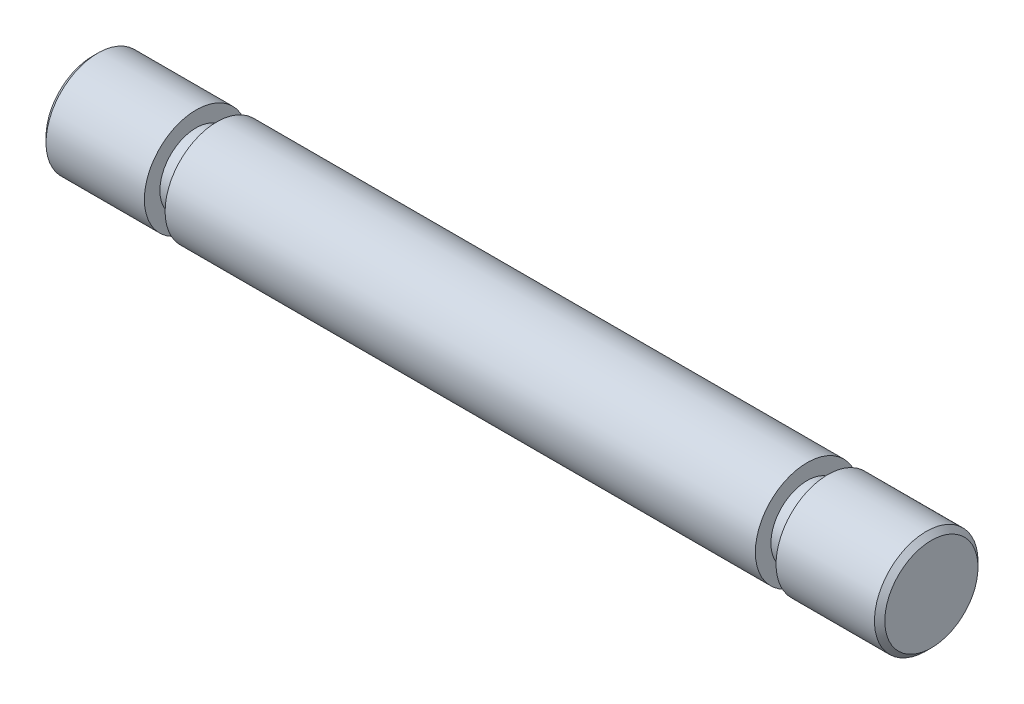
SolidWorks part; units mm, degrees
ref_plane "前视基准面" through (0, 0, 0) normal (0, 0, 1) x (1, 0, 0)
ref_plane "上视基准面" through (0, 0, 0) normal (0, 1, 0) x (1, 0, 0)
ref_plane "右视基准面" through (0, 0, 0) normal (1, 0, 0) x (0, 0, -1)
sketch "草图4" plane through (0, 0, 0) normal (1, 0, 0) x (0, 0, -1)
  circle A0 centre (0, 0) radius 5
  dimension "D1" = 10
extrude "凸台-拉伸4" add sketch "草图4" along normal blind 57
sketch "草图5" plane through (0, 0, 0) normal (-1, 0, 0) x (0, 0, 1)
  circle A0 centre (0, 0) radius 3.5
  dimension "D1" = 7
extrude "凸台-拉伸5" add sketch "草图5" along normal blind 2
sketch "草图6" plane through (-2, 0, 0) normal (-1, 0, 0) x (0, 0, 1)
  circle A0 centre (0, 0) radius 5
  dimension "D1" = 10
extrude "凸台-拉伸6" add sketch "草图6" along normal blind 10
sketch "草图7" plane through (57, 0, 0) normal (1, 0, 0) x (0, 0, -1)
  circle A0 centre (0, 0) radius 3.5
  dimension "D1" = 7
extrude "凸台-拉伸7" add sketch "草图7" along normal blind 2
sketch "草图8" plane through (59, 0, 0) normal (1, 0, 0) x (0, 0, -1)
  circle A0 centre (0, 0) radius 5
  dimension "D1" = 10
extrude "凸台-拉伸8" add sketch "草图8" along normal blind 10
chamfer "倒角1" distance 0.5 angle 45 2 edges at (-12, 0, 5) (69, 0, -5)
